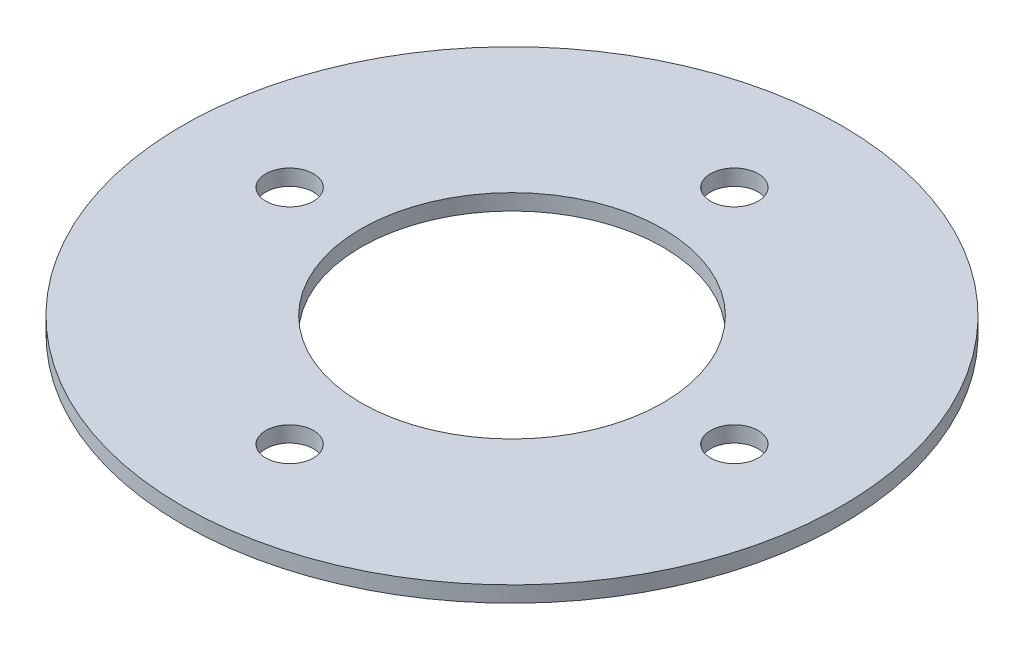
SolidWorks part; units mm, degrees
ref_plane "前视基准面" through (0, 0, 0) normal (0, 0, 1) x (1, 0, 0)
ref_plane "上视基准面" through (0, 0, 0) normal (0, 1, 0) x (1, 0, 0)
ref_plane "右视基准面" through (0, 0, 0) normal (1, 0, 0) x (0, 0, -1)
other "Configuration Table"
sketch "草图1" plane through (0, 0, 0) normal (0, 1, 0) x (1, 0, 0)
  circle A0 centre (0, 0) radius 20.75
  circle A1 centre (0, 0) radius 9.5
  circle A2 centre (14, 0) radius 1.5
  circle A3 centre (0, -14) radius 1.5
  circle A4 centre (-14, 0) radius 1.5
  circle A5 centre (0, 14) radius 1.5
  dimension "D1" = 41.5
  dimension "D2" = 19
  dimension "D3" = 3
  dimension "D4" = 14
extrude "凸台-拉伸2" add sketch "草图1" along normal blind 1 contours A0 A5 A4 A3 A2 A1
